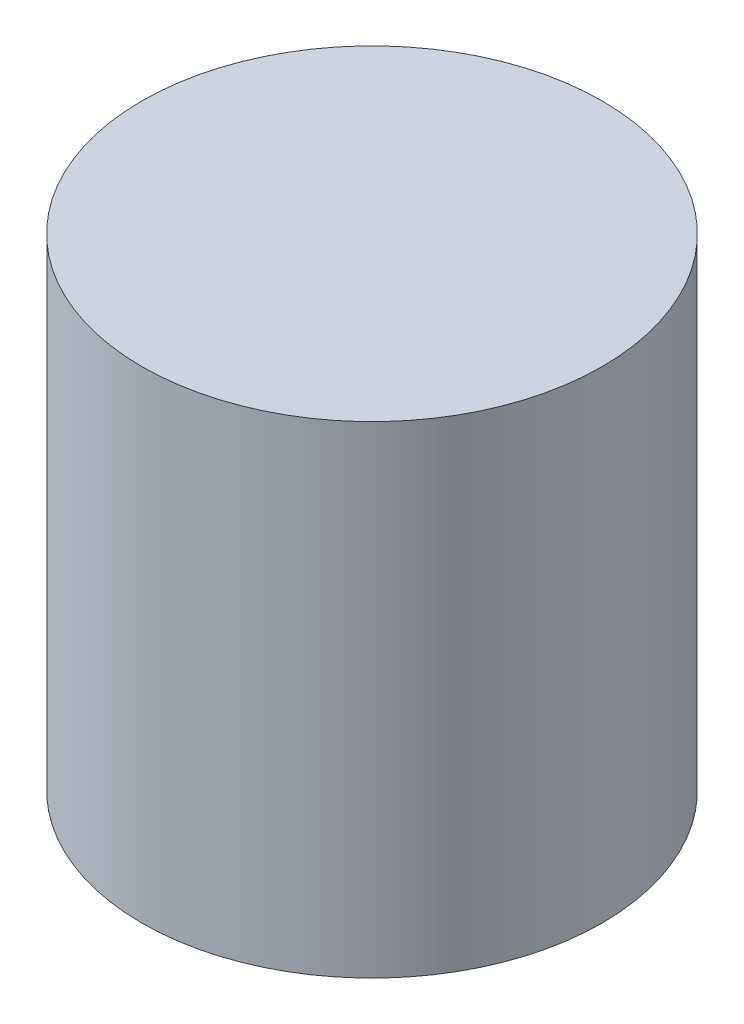
SolidWorks part; units mm, degrees
material "Fuel"
ref_plane "Front Plane" through (0, 0, 0) normal (0, 0, 1) x (1, 0, 0)
ref_plane "Top Plane" through (0, 0, 0) normal (0, 1, 0) x (1, 0, 0)
ref_plane "Right Plane" through (0, 0, 0) normal (1, 0, 0) x (0, 0, -1)
sketch "Sketch1" plane through (0, 0, 0) normal (0, 1, 0) x (1, 0, 0)
  circle A0 centre (0, 0) radius 4.775
  dimension "D1" = 9.55
extrude "Boss-Extrude1" add sketch "Sketch1" along normal mid plane 10
equation "\"EstCost\"=0.30*\"SW-Mass\""
